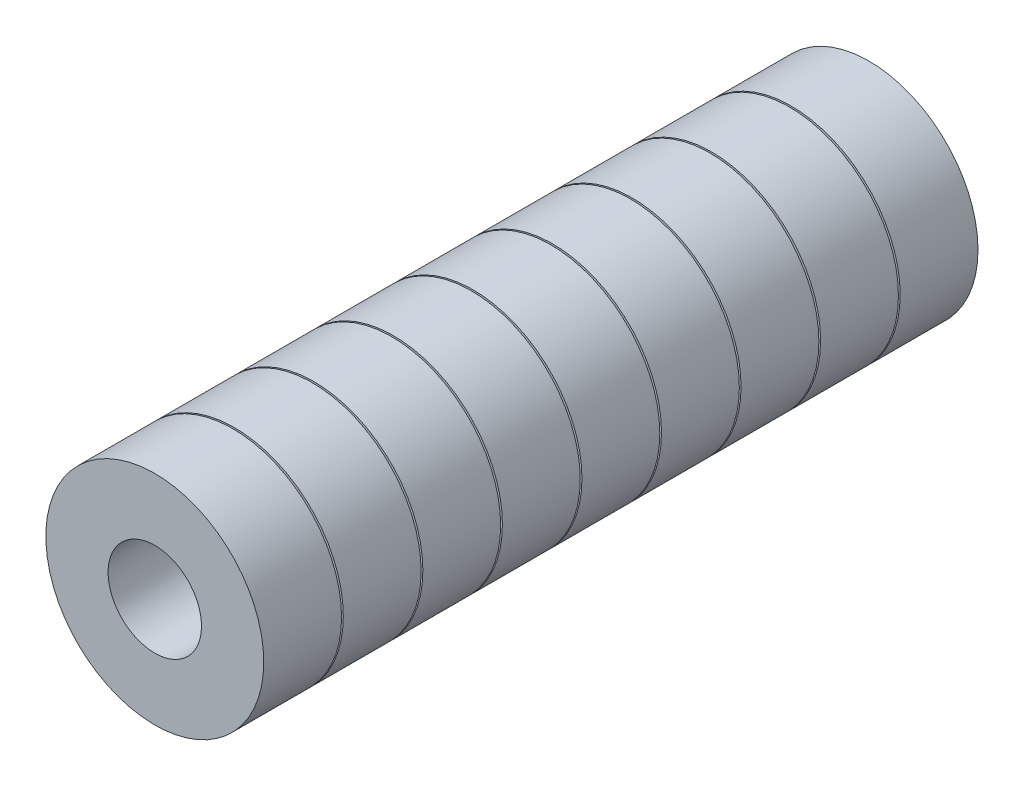
SolidWorks part; units mm, degrees
ref_plane "前视基准面" through (0, 0, 0) normal (0, 0, 1) x (1, 0, 0)
ref_plane "上视基准面" through (0, 0, 0) normal (0, 1, 0) x (1, 0, 0)
ref_plane "右视基准面" through (0, 0, 0) normal (1, 0, 0) x (0, 0, -1)
other "Configuration Table"
sketch "草图1" plane through (0, 0, 0) normal (0, 0, 1) x (1, 0, 0)
  circle A0 centre (0, 0) radius 3.5
  circle A1 centre (0, 0) radius 1.5
  dimension "D1" = 3
  dimension "D2" = 7
extrude "凸台-拉伸1" add sketch "草图1" along normal blind 2.5
pattern_linear "阵列(线性)1" count 9 spacing 2.5556 along (0, 0, -1) of bodies 106
